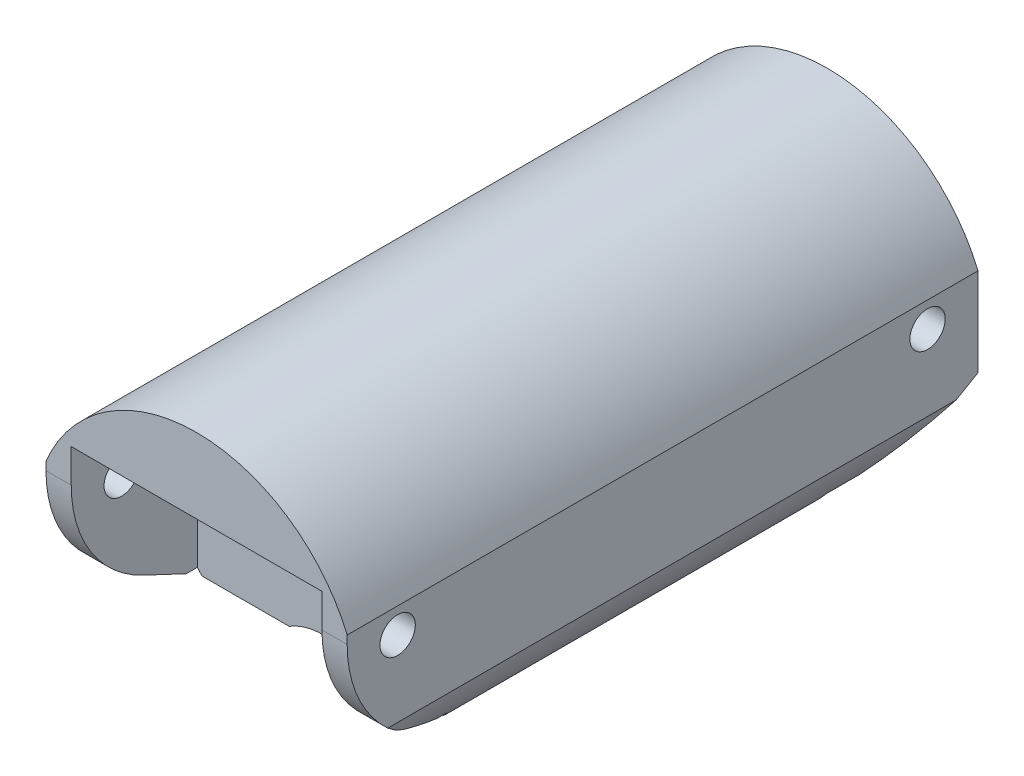
SolidWorks part; units mm, degrees
material "PET"
ref_plane "Front Plane" through (0, 0, 0) normal (0, 0, 1) x (1, 0, 0)
ref_plane "Top Plane" through (0, 0, 0) normal (0, 1, 0) x (1, 0, 0)
ref_plane "Right Plane" through (0, 0, 0) normal (1, 0, 0) x (0, 0, -1)
sketch "Sketch1" plane through (0, 0, 0) normal (0, 0, 1) x (1, 0, 0)
  line L0 (0, 0) -> (0, 5.08)
  line L3 (15.1587, 5.08) -> (15.1587, 0)
  arc A2 (0, 5.08) -> (15.1587, 5.08) centre (7.5794, 1.8999) cw
  arc A3 (0, 0) -> (15.1587, 0) centre (7.5794, 3.1801) ccw
  point P7 (7.5794, -5.0394)
  point P8 (7.5794, 10.1194)
extrude "Boss-Extrude1" add sketch "Sketch1" along normal mid plane 31.75 contours A2 L3 A3 L0
sketch "Sketch2" plane through (0, 0, 0) normal (1, 0, 0) x (0, 0, -1)
  line L4 (15.875, 2.54) -> (-49984.125, 2.54) construction
  line L5 (15.875, 5.08) -> (15.875, 0) construction
  line L6 (-15.875, 5.08) -> (-15.875, 0) construction
  line L7 (-15.875, -5.0394) -> (-15.875, 0.635)
  line L8 (-3.81, -5.0394) -> (-15.875, -5.0394)
  line L9 (-15.875, 0.635) -> (-3.81, -5.0394)
  line L10 (0, -1000) -> (0, 49000) construction
  line L18 (15.875, 0.635) -> (15.875, -5.0394)
  line L19 (-13.335, 1.27) -> (-15.875, 1.27)
  line L21 (-13.335, 3.81) -> (-15.875, 3.81)
  line L22 (-15.875, 1.27) -> (-15.875, 3.81)
  line L23 (-15.0884, 2.54) -> (-15.875, 3.81) construction
  line L24 (-15.0884, 2.54) -> (-15.875, 1.27) construction
  line L27 (13.335, 1.27) -> (15.875, 1.27)
  line L28 (15.875, 1.27) -> (15.875, 3.81)
  line L29 (13.335, 3.81) -> (15.875, 3.81)
  line L30 (15.875, -5.0394) -> (6.0467, -5.0394)
  line L31 (-15.875, -5.0394) -> (15.875, -5.0394) construction
  line L32 (6.0467, -5.0394) -> (15.875, 0.635)
  line L33 (-15.875, 10.1194) -> (-15.875, 5.08) construction
  arc A3 (-13.335, 3.81) -> (-13.335, 1.27) centre (-11.1353, 2.54) cw
  arc A4 (13.335, 3.81) -> (13.335, 1.27) centre (11.1353, 2.54) ccw
  point P0 (-15.0884, 2.54)
  point P11 (15.875, 2.54)
  point P14 (-15.875, 2.54)
  point P26 (-15.875, 2.54)
extrude "Cut-Extrude1" cut sketch "Sketch2" along normal through all
sketch "Sketch3" plane through (0, 0, 15.875) normal (0, 0, 1) x (1, 0, 0)
  line L3 (-12.7761, 2.54) -> (35.5855, 2.54) construction
  line L4 (7.5794, 9.0576) -> (7.5794, -5.0394) construction
  line L5 (16.1544, 2.54) -> (0, 2.54) construction
  line L6 (15.1587, 2.54) -> (0, 2.54) construction
  line L7 (0, 5.08) -> (0, 0) construction
  arc A3 (15.1587, 5.08) -> (0, 5.08) centre (7.5794, 1.8999) ccw construction
  arc A5 (13.918, 4.7488) -> (0.9396, 3.9515) centre (7.5794, 1.8999) ccw
  arc A7 (0, 0) -> (15.1587, 0) centre (7.5794, 3.1801) ccw construction
  arc A9 (13.918, 0.3312) -> (0.9396, 1.1285) centre (7.5794, 3.1801) cw
  arc A11 (15.1587, 5.08) -> (0, 5.08) centre (7.5794, 1.8999) ccw
  arc A12 (4.9537, 8.3343) -> (10.205, 8.3343) centre (7.5794, 10.1194) ccw
  arc A13 (4.9537, -3.2543) -> (10.205, -3.2543) centre (7.5794, -5.0394) cw
  point P14 (7.5794, 6.9444)
  dimension "D1" = 1.27
  dimension "D2" = 3.175
extrude "Cut-Extrude2" cut sketch "Sketch3" against normal through all contours A13 A9
sketch "Sketch4" plane through (0, 0, 0) normal (-1, 0, 0) x (0, 0, 1)
  line L0 (15.875, 1.27) -> (13.335, 1.27) construction
  line L1 (13.335, 3.81) -> (15.875, 3.81) construction
  line L2 (-13.335, 1.27) -> (-15.875, 1.27) construction
  line L3 (-15.875, 3.81) -> (-13.335, 3.81) construction
  line L4 (15.875, 1.27) -> (13.335, 1.27)
  line L5 (13.335, 3.81) -> (15.875, 3.81)
  line L6 (-13.335, 1.27) -> (-15.875, 1.27)
  line L7 (-15.875, 3.81) -> (-13.335, 3.81)
  line L8 (-15.875, 3.81) -> (-15.875, 1.27)
  line L9 (15.875, 3.81) -> (15.875, 1.27)
  arc A0 (11.1353, 0) -> (13.335, 1.27) centre (11.1353, 2.54) ccw construction
  arc A1 (13.335, 3.81) -> (11.1353, 5.08) centre (11.1353, 2.54) ccw construction
  arc A2 (11.1353, 5.08) -> (11.1353, 0) centre (11.1353, 2.54) ccw construction
  arc A3 (-13.335, 1.27) -> (-11.1353, 0) centre (-11.1353, 2.54) ccw construction
  arc A4 (-11.1353, 5.08) -> (-13.335, 3.81) centre (-11.1353, 2.54) ccw construction
  arc A5 (-11.1353, 0) -> (-11.1353, 5.08) centre (-11.1353, 2.54) ccw construction
  arc A6 (11.1353, 0) -> (13.335, 1.27) centre (11.1353, 2.54) ccw
  arc A7 (13.335, 3.81) -> (11.1353, 5.08) centre (11.1353, 2.54) ccw
  arc A8 (11.1353, 5.08) -> (11.1353, 0) centre (11.1353, 2.54) ccw
  arc A9 (-13.335, 1.27) -> (-11.1353, 0) centre (-11.1353, 2.54) ccw
  arc A10 (-11.1353, 5.08) -> (-13.335, 3.81) centre (-11.1353, 2.54) ccw
  arc A11 (-11.1353, 0) -> (-11.1353, 5.08) centre (-11.1353, 2.54) ccw
extrude "Boss-Extrude2" add sketch "Sketch4" against normal up to surface (15.1587 mm away) up to face at (15.1587, 2.54, 0)
ref_plane "Plane1" through (5.08, 0, 0) normal (-1, 0, 0) x (0, 0, 1)
ref_plane "Plane2" through (7.5794, 0, 0) normal (1, 0, 0) x (0, 0, -1)
ref_plane "Plane3" through (0, -5.08, 0) normal (0, 1, 0) x (1, 0, 0)
sketch "Sketch6" plane through (0, -5.08, 0) normal (0, 1, 0) x (1, 0, 0)
  line L0 (15.1587, -15.875) -> (0, -15.875) construction
  line L1 (1.27, -15.875) -> (13.8887, -15.875)
  line L2 (1.27, -15.875) -> (1.27, -9.525)
  line L3 (1.27, -9.525) -> (13.8887, -9.525)
  line L4 (13.8887, -15.875) -> (13.8887, -9.525)
  line L5 (0, -15.875) -> (0, 15.875)
  line L9 (13.8887, -15.875) -> (13.8887, -10.0855)
  line L10 (-14.5241, 0) -> (35.8688, 0) construction
  line L12 (13.8887, 15.875) -> (13.8887, 9.525)
  line L15 (1.27, 9.525) -> (13.8887, 9.525)
  line L17 (1.27, 15.875) -> (13.8887, 15.875)
  line L18 (1.27, 15.875) -> (1.27, 9.525)
  line L20 (15.1587, -14.5248) -> (15.1587, 14.7751) construction
  ellipse E0 centre (7.5794, -21.2865) end of major axis (7.5794, -3.81) minor radius 8.2195 (15.1587, -14.5248) -> (0, -14.5248) ccw construction
  dimension "D1" = 1.27
  dimension "D2" = 1.27
  dimension "D3" = 6.35
extrude "Cut-Extrude3" cut sketch "Sketch6" along normal blind 11.43
sketch "Sketch7" plane through (0, 0, 0) normal (-1, 0, 0) x (0, 0, 1)
  line L0 (14.5248, 0) -> (-14.7751, 0) construction
  line L1 (15.875, 5.08) -> (15.875, 0.635) construction
  line L2 (0, 16.8488) -> (0, -13.3412) construction
  circle A0 centre (13.335, 3.81) radius 0.889
  circle A1 centre (-13.335, 3.81) radius 0.889
  dimension "D1" = 3.81
  dimension "D3" = 1.778
  dimension "D2" = 2.54
extrude "Cut-Extrude4" cut sketch "Sketch7" against normal through all
sketch "Sketch8" plane through (0, 0, -9.525) normal (0, 0, -1) x (-1, 0, 0)
  line L1 (-10.2464, 0.5486) -> (-4.9124, 0.5486) construction
  line L2 (-10.2464, 0.5486) -> (-10.2464, 6.2382) construction
  line L3 (-4.9124, 5.8572) -> (-5.5474, 5.8572) construction
  line L4 (-4.9124, 5.4762) -> (-5.5474, 5.4762)
  line L5 (-4.9124, 6.2382) -> (-5.5474, 6.2382)
  line L6 (-10.2464, 6.2382) -> (-4.9124, 6.2382) construction
  line L7 (-4.9124, 0.5486) -> (-4.9124, 6.2382) construction
  line L8 (-10.2464, 0.5486) -> (-4.9124, 6.2382) construction
  line L9 (-10.2464, 6.2382) -> (-4.9124, 0.5486) construction
  line L10 (-1.27, 6.35) -> (-13.8887, 6.35) construction
  line L11 (-1.27, 6.35) -> (-13.8887, 6.35) construction
  line L12 (-20.0888, -1.8644) -> (7.885, -1.8644) construction
  arc A1 (-4.9124, 5.4762) -> (-4.9124, 6.2382) centre (-4.9124, 5.8572) ccw
  arc A2 (-5.5474, 6.2382) -> (-5.5474, 5.4762) centre (-5.5474, 5.8572) ccw
  arc A3 (-5.1201, -3.0312) -> (-10.0386, -3.0312) centre (-7.5794, -5.0394) ccw construction
  arc A4 (-5.1201, -3.0312) -> (-10.0386, -3.0312) centre (-7.5794, -5.0394) ccw
  point P2 (-5.2299, 5.8572)
  point P7 (-7.5794, 3.3934)
  point P17 (-7.5794, 6.35)
  point P21 (-7.5794, -1.8644)
  dimension "D1" = 0.762
  dimension "D2" = 0.635
  dimension "D3" = 5.334
  dimension "D4" = 5.6896
  dimension "D5" = 2.413
extrude "Cut-Extrude5" cut sketch "Sketch8" against normal blind 15.875 contours L5 A2 L4 A1
fillet "Fillet1" radius 6.35 2 edges at (0.635, 0.635, 15.875) (14.5237, 0.635, 15.875)
sketch "Sketch9" plane through (0, 0, 9.525) normal (0, 0, 1) x (1, 0, 0)
  line L0 (9.2693, -2.3515) -> (13.6589, -2.3515) construction
  line L1 (4.9124, 6.7671) -> (10.2464, 6.7671)
  line L2 (4.9124, 6.7671) -> (4.9124, 1.0775)
  line L3 (4.9124, 1.0775) -> (10.2464, 1.0775)
  line L4 (10.2464, 6.7671) -> (10.2464, 1.0775)
  line L5 (4.9124, 6.7671) -> (10.2464, 1.0775) construction
  line L6 (4.9124, 1.0775) -> (10.2464, 6.7671) construction
  line L7 (9.6114, 6.3861) -> (10.2464, 6.3861) construction
  line L8 (9.6114, 6.7671) -> (10.2464, 6.7671)
  line L9 (9.6114, 6.0051) -> (10.2464, 6.0051)
  line L10 (1.27, 6.35) -> (13.8887, 6.35) construction
  line L11 (1.27, 6.35) -> (13.8887, 6.35)
  arc A0 (9.6114, 6.7671) -> (9.6114, 6.0051) centre (9.6114, 6.3861) ccw
  arc A1 (10.2464, 6.0051) -> (10.2464, 6.7671) centre (10.2464, 6.3861) ccw
  point P0 (7.5794, 3.9223)
  point P9 (9.9289, 6.3861)
  point P19 (7.5794, 6.35)
  dimension "D1" = 5.334
  dimension "D2" = 5.6896
  dimension "D3" = 3.429
  dimension "D4" = 0.635
  dimension "D5" = 0.762
extrude "Cut-Extrude6" cut sketch "Sketch9" against normal blind 17.78 contours L9 A1 L8 A0
sketch "Sketch10" plane through (0, 0, 0) normal (-1, 0, 0) x (0, 0, 1)
  text T0 "Pointer 2\r\n"
extrude "Cut-Extrude7" cut sketch "Sketch10" against normal blind 1
equation "\"D1@Sketch1\"=0.5968"
equation "\"D2@Sketch1\"=0.5968"
equation "\"D1@Boss-Extrude1\"=1.25"
equation "\"D2@Sketch2\"=0.1"
equation "\"D3@Sketch2\"=0.1"
